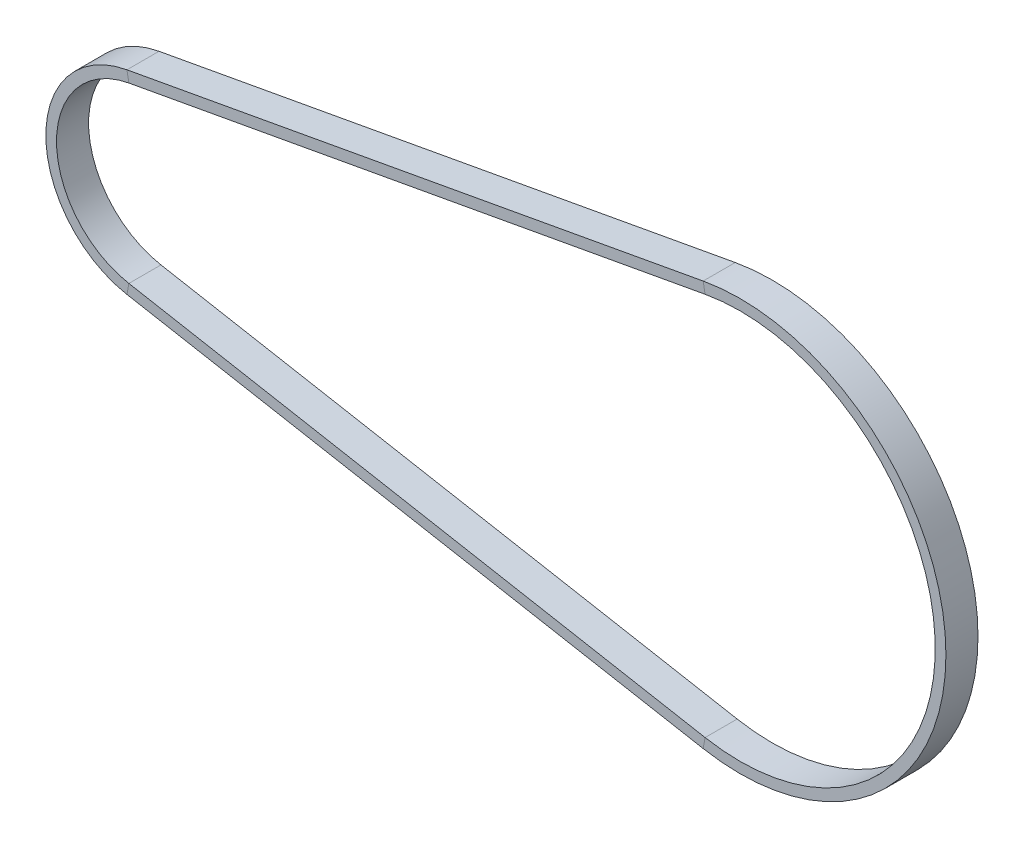
SolidWorks part; units mm, degrees
ref_plane "Plano frontal" through (0, 0, 0) normal (0, 0, 1) x (1, 0, 0)
ref_plane "Plano superior" through (0, 0, 0) normal (0, 1, 0) x (1, 0, 0)
ref_plane "Plano direito" through (0, 0, 0) normal (1, 0, 0) x (0, 0, -1)
sketch "Esboço1" plane through (0, 0, 0) normal (0, 0, 1) x (1, 0, 0)
  line L0 (-60.4629, 17.2156) -> (47.3303, 36.8905)
  line L2 (-60.4629, -17.2156) -> (47.3303, -36.8905)
  arc A0 (-60.4629, 17.2156) -> (-60.4629, -17.2156) centre (-57.3206, 0) ccw
  arc A1 (47.3303, -36.8905) -> (47.3303, 36.8905) centre (54.0637, 0) ccw
  point P1 (0, 0)
  dimension "D1" = 35
  dimension "D2" = 75
ref_plane "Plano1" through (-60.4629, 17.2156, 0) normal (0.9837, 0.1796, 0) x (0, 0, -1)
sketch "Esboço2" plane through (-60.4629, 17.2156, 0) normal (0.9837, 0.1796, 0) x (0, 0, -1)
  line L0 (0, 0) -> (0, -75) construction
  line L1 (-3, -1) -> (3, -1)
  line L2 (-3, -1) -> (-3, 1)
  line L3 (-3, 1) -> (3, 1)
  line L4 (3, -1) -> (3, 1)
  line L5 (-3, -1) -> (3, 1) construction
  line L6 (-3, 1) -> (3, -1) construction
  line L7 (0, 0) -> (0, -33.8716) construction
  point P0 (0, 0)
  point P9 (0, 1)
  point P11 (0, 0)
  point P15 (0, -1)
  dimension "D1" = 2
  dimension "D2" = 6
  dimension "D3" = 1
sweep "Varredura1" add profiles "Esboço2" path "Esboço1"
